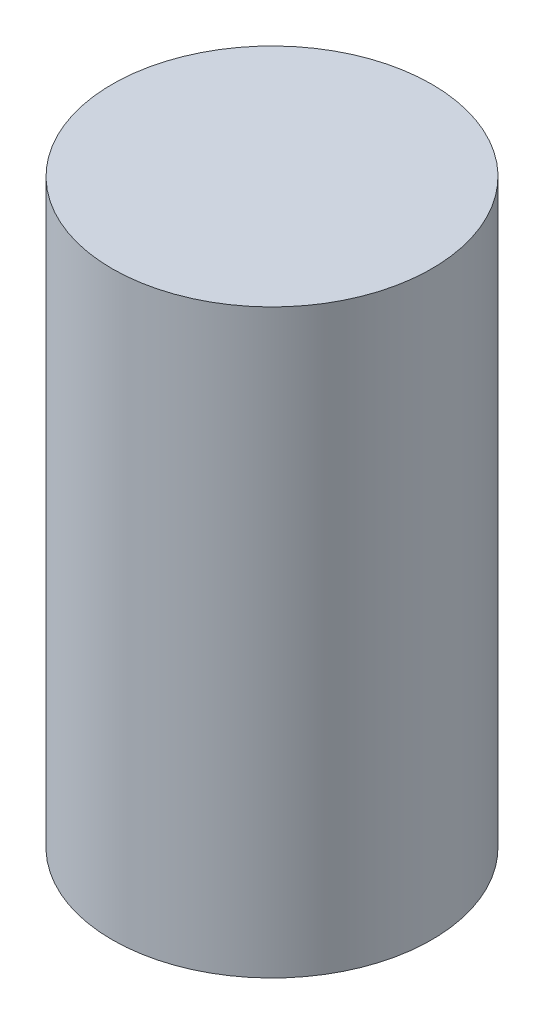
SolidWorks part; units mm, degrees
material "LAB 1 FEA"
ref_plane "Front Plane" through (0, 0, 0) normal (0, 0, 1) x (1, 0, 0)
ref_plane "Top Plane" through (0, 0, 0) normal (0, 1, 0) x (1, 0, 0)
ref_plane "Right Plane" through (0, 0, 0) normal (1, 0, 0) x (0, 0, -1)
sketch "Sketch1" plane through (0, 0, 0) normal (0, 1, 0) x (1, 0, 0)
  circle A0 centre (0, 0) radius 13.75
  dimension "D1" = 27.5
extrude "Boss-Extrude1" add sketch "Sketch1" along normal blind 50
